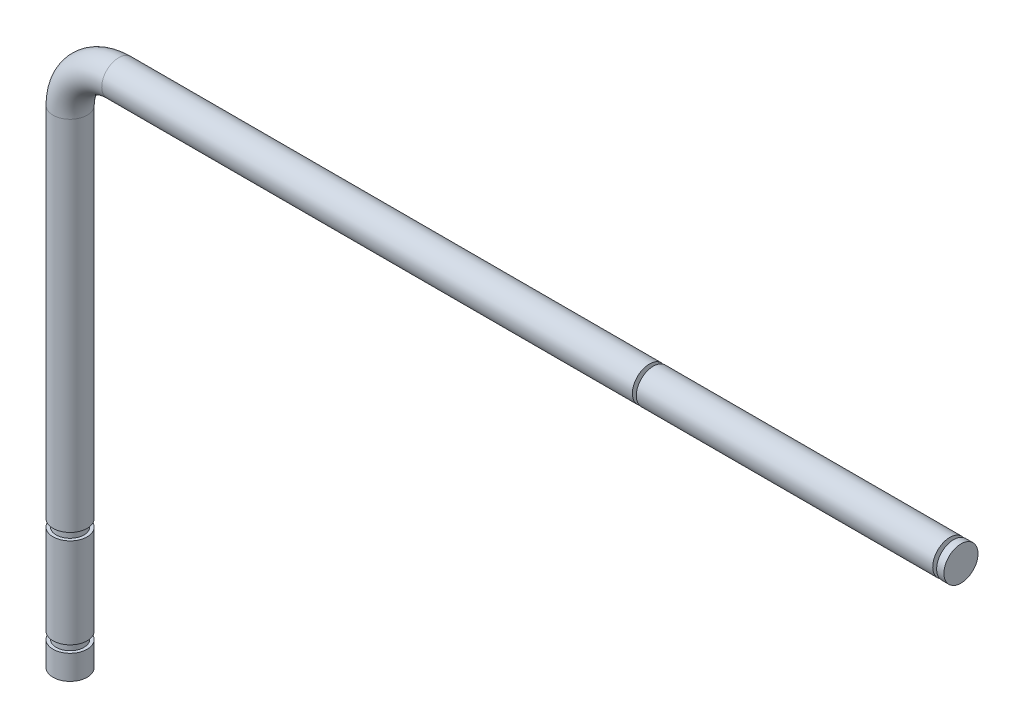
SolidWorks part; units mm, degrees
material "Stal węglowa"
ref_plane "Płaszczyzna przednia" through (0, 0, 0) normal (0, 0, 1) x (1, 0, 0)
ref_plane "Płaszczyzna górna" through (0, 0, 0) normal (0, 1, 0) x (1, 0, 0)
ref_plane "Płaszczyzna prawa" through (0, 0, 0) normal (1, 0, 0) x (0, 0, -1)
sketch "Szkic1" plane through (0, 0, 0) normal (0, 0, 1) x (1, 0, 0)
  line L0 (10, 0) -> (183, 0)
  line L1 (0, -10) -> (0, -110)
  arc A0 (10, 0) -> (0, -10) centre (10, -10) ccw
  point P6 (0, 0)
  dimension "D3" = 10
  dimension "D1" = 183
  dimension "D2" = 110
sweep "Wyciągnięcie po ścieżce1" add path "Szkic1" circular profile diameter 7 parameters "D3"=7
ref_plane "Płaszczyzna2" through (0, -105, 0) normal (0, -1, 0) x (-1, 0, 0)
sketch "Szkic26" plane through (0, -105, 0) normal (0, -1, 0) x (-1, 0, 0)
  circle A0 centre (0, 0) radius 2.85
  circle A1 centre (0, 0) radius 4
  dimension "D1" = 5.7
  dimension "D2" = 8
extrude "Wytnij-wyciągnięcie1" cut sketch "Szkic26" against normal blind 1.5
ref_plane "Płaszczyzna8" through (0, -85, 0) normal (0, -1, 0) x (-1, 0, 0)
sketch "Szkic36" plane through (0, -85, 0) normal (0, -1, 0) x (-1, 0, 0)
  circle A0 centre (0, 0) radius 2.85
  circle A1 centre (0, 0) radius 4
  dimension "D1" = 5.7
  dimension "D2" = 8
extrude "Wytnij-wyciągnięcie3" cut sketch "Szkic36" against normal blind 1.5
ref_plane "Płaszczyzna10" through (181.5, 0, 0) normal (1, 0, 0) x (0, 0, -1)
sketch "Szkic46" plane through (181.5, 0, 0) normal (1, 0, 0) x (0, 0, -1)
  circle A0 centre (0, 0) radius 4
  circle A1 centre (0, 0) radius 1.6
  dimension "D1" = 3.2
  dimension "D2" = 8
extrude "Wytnij-wyciągnięcie4" cut sketch "Szkic46" against normal blind 0.8
ref_plane "Płaszczyzna11" through (119, 0, 0) normal (1, 0, 0) x (0, 0, -1)
sketch "Szkic53" plane through (119, 0, 0) normal (1, 0, 0) x (0, 0, -1)
  circle A0 centre (0, 0) radius 4
  circle A1 centre (0, 0) radius 1.6
  dimension "D1" = 8
  dimension "D2" = 3.2
extrude "Wytnij-wyciągnięcie5" cut sketch "Szkic53" along normal blind 0.8
ref_plane "Płaszczyzna12" through (0, -110, 0) normal (0, -1, 0) x (-1, 0, 0)
sketch "Szkic54" plane through (0, -110, 0) normal (0, -1, 0) x (-1, 0, 0)
  circle A0 centre (0, 0) radius 1.25
  dimension "D1" = 2.5
extrude "Wytnij-wyciągnięcie6" cut sketch "Szkic54" against normal blind 10
